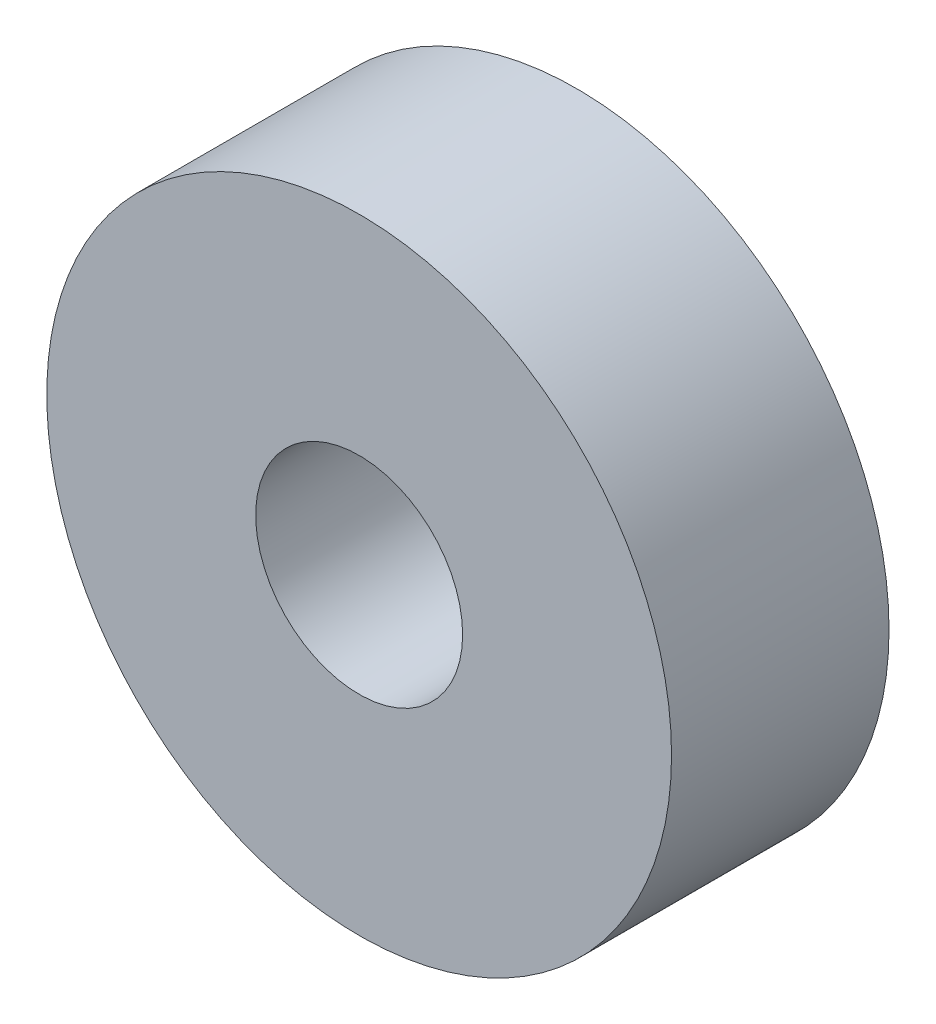
SolidWorks part; units mm, degrees
material "Plain Carbon Steel"
ref_plane "Front" through (0, 0, 0) normal (0, 0, 1) x (1, 0, 0)
ref_plane "Top" through (0, 0, 0) normal (0, 1, 0) x (1, 0, 0)
ref_plane "Right" through (0, 0, 0) normal (1, 0, 0) x (0, 0, -1)
sketch "Sketch1" plane through (0, 0, 0) normal (0, 0, 1) x (1, 0, 0)
  circle A0 centre (0, 0) radius 14.3002
  circle A1 centre (0, 0) radius 4.7371
  dimension "D1" = 9.4742
  dimension "D2" = 28.6004
extrude "Extrude1" add sketch "Sketch1" along normal blind 9.9568
